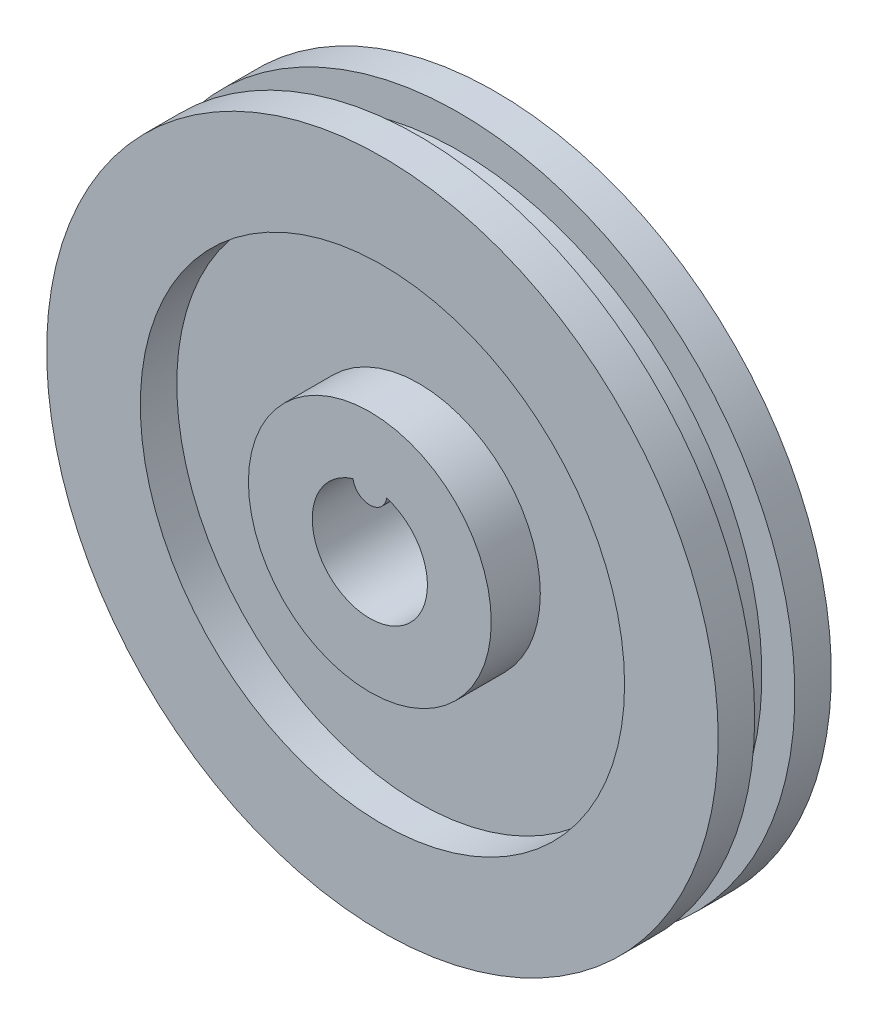
SolidWorks part; units mm, degrees
ref_plane "Front Plane" through (0, 0, 0) normal (0, 0, 1) x (1, 0, 0)
ref_plane "Top Plane" through (0, 0, 0) normal (0, 1, 0) x (1, 0, 0)
ref_plane "Right Plane" through (0, 0, 0) normal (1, 0, 0) x (0, 0, -1)
sketch "Sketch1" plane through (0, 0, 0) normal (0, 0, 1) x (1, 0, 0)
  line L0 (0, 16.8122) -> (0, -16.2324) construction
  line L1 (-11.5469, 0) -> (8.9047, 0) construction
  arc A0 (-1.2264, 4.017) -> (1.2264, 4.017) centre (0, 0) ccw
  circle A1 centre (0, 0) radius 8.855
  arc A2 (-1.2264, 4.017) -> (1.2264, 4.017) centre (0, 4.2) ccw
  dimension "D1" = 8.4
  dimension "D2" = 17.71
  dimension "D3" = 1.24
extrude "Boss-Extrude1" add sketch "Sketch1" along normal mid plane 10.09
sketch "Sketch2" plane through (0, 0, 0) normal (0, 0, 1) x (1, 0, 0)
  circle A0 centre (0, 0) radius 22.085
  circle A1 centre (0, 0) radius 8.855
  dimension "D1" = 44.17
extrude "Boss-Extrude2" add sketch "Sketch2" along normal mid plane 2.93
sketch "Sketch4" plane through (0, 0, 1.465) normal (0, 0, 1) x (1, 0, 0)
  circle A0 centre (0, 0) radius 24.49
  circle A1 centre (0, 0) radius 17.66
extrude "Boss-Extrude3" add sketch "Sketch4" along normal blind 2.66
sketch "Sketch5" plane through (0, 0, -1.465) normal (0, 0, -1) x (-1, 0, 0)
  circle A0 centre (0, 0) radius 17.66
  circle A1 centre (0, 0) radius 24.49
extrude "Boss-Extrude4" add sketch "Sketch5" along normal blind 2.66
